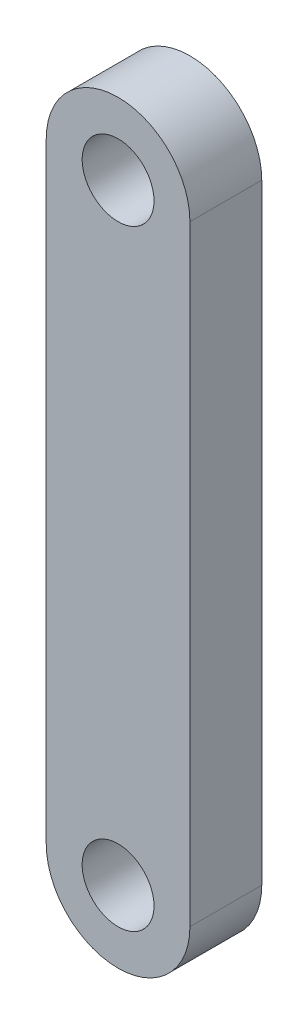
SolidWorks part; units mm, degrees
ref_plane "Alzado" through (0, 0, 0) normal (0, 0, 1) x (1, 0, 0)
ref_plane "Planta" through (0, 0, 0) normal (0, 1, 0) x (1, 0, 0)
ref_plane "Vista lateral" through (0, 0, 0) normal (1, 0, 0) x (0, 0, -1)
sketch "Croquis1" plane through (0, 0, 0) normal (0, 0, 1) x (1, 0, 0)
  line L2 (0, 0) -> (0, -17)
  line L4 (4, 0) -> (4, -17)
  arc A0 (4, 0) -> (0, 0) centre (2, 0) ccw
  arc A1 (0, -17) -> (4, -17) centre (2, -17) ccw
  circle A2 centre (2, 0) radius 1
  circle A3 centre (2, -17) radius 1
  dimension "D3" = 2
  dimension "D4" = 2
  dimension "D6" = 2
  dimension "D2" = 4
  dimension "D5" = 17
extrude "Saliente-Extruir1" add sketch "Croquis1" along normal blind 2
